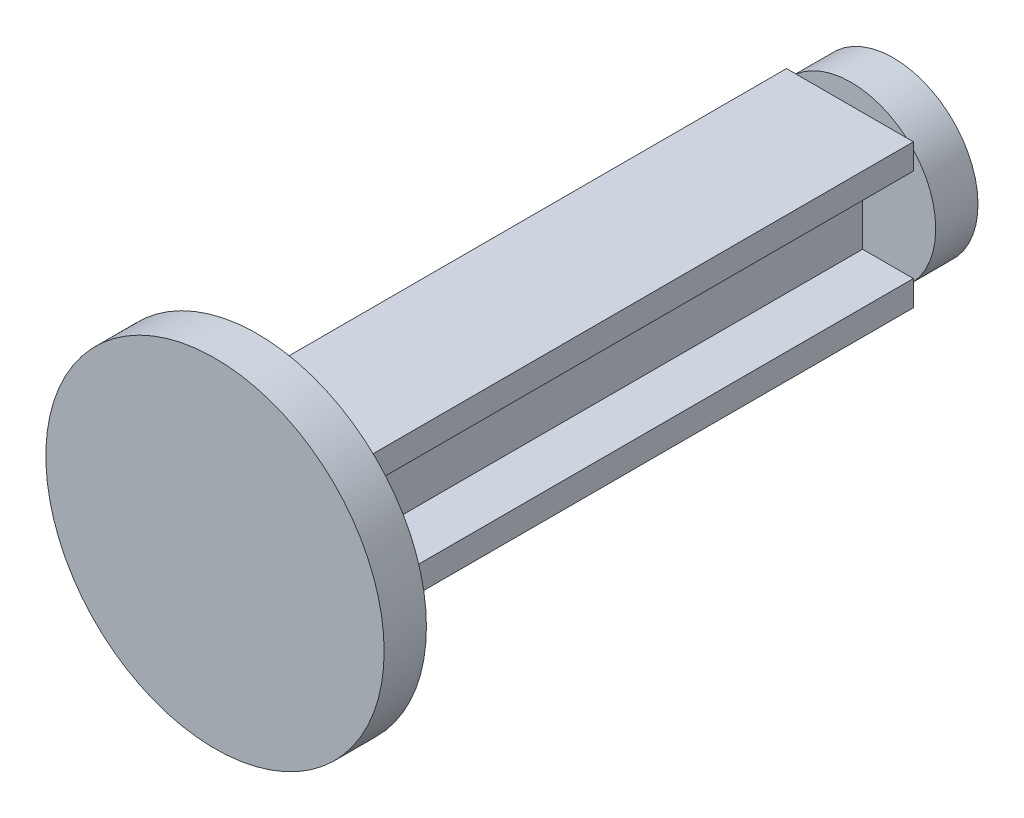
SolidWorks part; units mm, degrees
material "Plain Carbon Steel"
ref_plane "Front Plane" through (0, 0, 0) normal (0, 0, 1) x (1, 0, 0)
ref_plane "Top Plane" through (0, 0, 0) normal (0, 1, 0) x (1, 0, 0)
ref_plane "Right Plane" through (0, 0, 0) normal (1, 0, 0) x (0, 0, -1)
sketch "Sketch4" plane through (1.7618, -4.4283, 0) normal (0, 0, 1) x (1, 0, 0)
  line L1 (-25.6413, 19.5929) -> (4.3587, 19.5929)
  line L2 (-25.6413, 19.5929) -> (-25.6413, 13.5929)
  line L3 (-25.6413, 13.5929) -> (4.3587, 13.5929)
  line L4 (4.3587, 19.5929) -> (4.3587, 13.5929)
  line L5 (-25.6413, -8.4071) -> (4.3587, -8.4071)
  line L6 (-25.6413, -8.4071) -> (-25.6413, -14.4071)
  line L7 (-25.6413, -14.4071) -> (4.3587, -14.4071)
  line L8 (4.3587, -8.4071) -> (4.3587, -14.4071)
  line L9 (-13.6413, 13.5929) -> (-7.6413, 13.5929)
  line L10 (-13.6413, 13.5929) -> (-13.6413, -8.4071)
  line L11 (-13.6413, -8.4071) -> (-7.6413, -8.4071)
  line L12 (-7.6413, 13.5929) -> (-7.6413, -8.4071)
  point P12 (-7.6413, 2.5929)
  dimension "D1" = 6
  dimension "D2" = 30
  dimension "D3" = 30
  dimension "D4" = 6
  dimension "D5" = 6
  dimension "D6" = 12
  dimension "D7" = 12
  dimension "D8" = 34
extrude "Boss-Extrude1" add sketch "Sketch4" along normal blind 140 contours L4 L1 L2 L3 | L12 L3 L10 L5 | L8 L5 L6 L7
sketch "Sketch6" plane through (0, 0, 0) normal (0, 0, -1) x (-1, 0, 0)
  circle A1 centre (8.5938, 0) radius 20
  dimension "D1" = 40
extrude "Boss-Extrude2" add sketch "Sketch6" along normal blind 10 contours A1
sketch "Sketch7" plane through (0, 0, 140) normal (0, 0, 1) x (1, 0, 0)
  circle A0 centre (-9.032, -1.7185) radius 40
  dimension "D1" = 80
extrude "Boss-Extrude3" add sketch "Sketch7" along normal blind 10 contours A0
